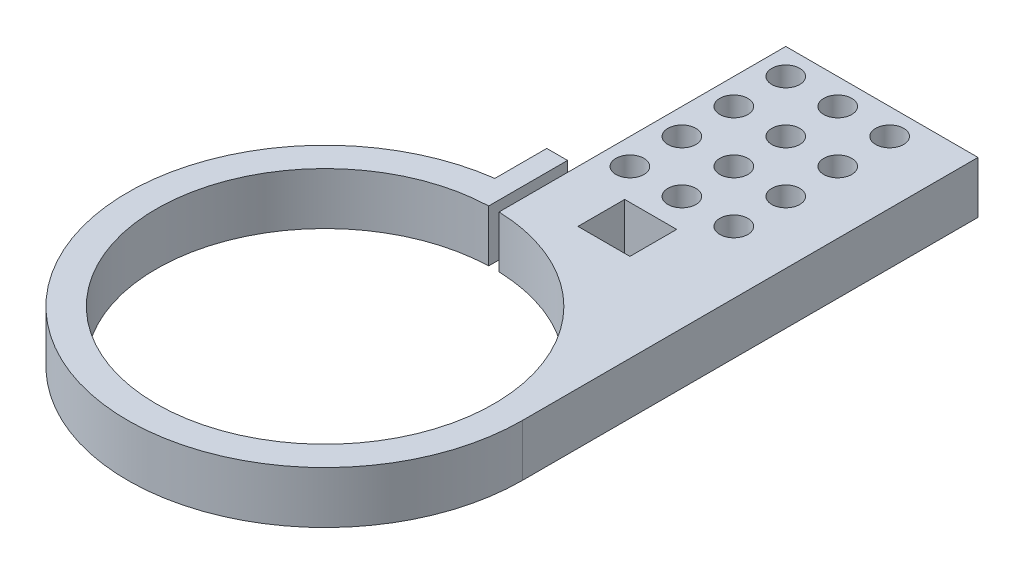
SolidWorks part; units mm, degrees
ref_plane "Front Plane" through (0, 0, 0) normal (0, 0, 1) x (1, 0, 0)
ref_plane "Top Plane" through (0, 0, 0) normal (0, 1, 0) x (1, 0, 0)
ref_plane "Right Plane" through (0, 0, 0) normal (1, 0, 0) x (0, 0, -1)
sketch "Sketch1" plane through (0, 0, 0) normal (0, 1, 0) x (1, 0, 0)
  circle A0 centre (0, 0) radius 41.275
  circle A1 centre (0, 0) radius 48.26
  dimension "D1" = 82.55
  dimension "D2" = 96.52
extrude "Boss-Extrude1" add sketch "Sketch1" along normal blind 12.7
sketch "Sketch2" plane through (0, 0, 0) normal (0, 1, 0) x (1, 0, 0)
  line L1 (6.35, 60.5404) -> (-6.35, 60.5404)
  line L2 (6.35, 60.5404) -> (6.35, 47.8404)
  line L3 (6.35, 47.8404) -> (-6.35, 47.8404)
  line L4 (-6.35, 60.5404) -> (-6.35, 47.8404)
  line L5 (6.35, 60.5404) -> (-6.35, 47.8404) construction
  line L6 (6.35, 47.8404) -> (-6.35, 60.5404) construction
  circle A0 centre (0, 0) radius 48.26 construction
  point P0 (0, 54.1904)
  dimension "D1" = 12.7
  dimension "D2" = 12.7
extrude "Boss-Extrude2" add sketch "Sketch2" along normal blind 12.7
sketch "Sketch4" plane through (0, 0, 0) normal (0, 1, 0) x (1, 0, 0)
  line L1 (-1.27, 38.0719) -> (1.27, 38.0719)
  line L2 (-1.27, 38.0719) -> (-1.27, 82.1708)
  line L3 (-1.27, 82.1708) -> (1.27, 82.1708)
  line L4 (1.27, 38.0719) -> (1.27, 82.1708)
  line L5 (-1.27, 38.0719) -> (1.27, 82.1708) construction
  line L6 (-1.27, 82.1708) -> (1.27, 38.0719) construction
  point P0 (0, 60.1213)
  point P5 (0, 82.1708)
  dimension "D1" = 2.54
extrude "Cut-Extrude2" cut sketch "Sketch4" along normal through all
sketch "Sketch5" plane through (0, 0, 0) normal (1, 0, 0) x (0, 0, -1)
  line L1 (60.5404, 12.7) -> (0, 12.7)
  line L2 (60.5404, 12.7) -> (60.5404, 0)
  line L3 (60.5404, 0) -> (0, 0)
  line L4 (0, 12.7) -> (0, 0)
extrude "Boss-Extrude3" add sketch "Sketch5" against normal up to next from offset 48.26
sketch "Sketch6" plane through (0, 12.7, 0) normal (0, 1, 0) x (1, 0, 0)
  line L0 (1.27, 41.2555) -> (1.27, 60.5404) construction
  line L1 (48.26, 60.5404) -> (1.27, 60.5404)
  line L2 (48.26, 60.5404) -> (48.26, 111.3404)
  line L3 (48.26, 111.3404) -> (1.27, 111.3404)
  line L4 (1.27, 60.5404) -> (1.27, 111.3404)
  dimension "D1" = 50.8
extrude "Boss-Extrude4" add sketch "Sketch6" against normal blind 12.7
sketch "Sketch7" plane through (0, 0, 0) normal (0, 1, 0) x (1, 0, 0)
  line L0 (48.26, 111.3404) -> (1.27, 111.3404) construction
  line L2 (1.27, 41.2555) -> (1.27, 111.3404) construction
  line L4 (13.97, 59.2704) -> (26.67, 59.2704)
  line L5 (13.97, 59.2704) -> (13.97, 47.8404)
  line L6 (13.97, 47.8404) -> (26.67, 47.8404)
  line L7 (26.67, 59.2704) -> (26.67, 47.8404)
  circle A0 centre (7.62, 104.9904) radius 3.429
  circle A1 centre (20.32, 104.9904) radius 3.429
  circle A2 centre (20.32, 92.2904) radius 3.429
  circle A3 centre (7.62, 92.2904) radius 3.429
  circle A4 centre (7.62, 79.5904) radius 3.429
  circle A5 centre (20.32, 79.5904) radius 3.429
  circle A6 centre (7.62, 66.8904) radius 3.429
  circle A7 centre (20.32, 66.8904) radius 3.429
  circle A8 centre (33.02, 104.9904) radius 3.429
  circle A9 centre (33.02, 92.2904) radius 3.429
  circle A10 centre (33.02, 79.5904) radius 3.429
  circle A11 centre (33.02, 66.8904) radius 3.429
  dimension "D1" = 6.858
  dimension "D9" = 12.7
  dimension "D10" = 12.7
  dimension "D2" = 6.35
  dimension "D3" = 6.35
  dimension "D6" = 11.43
  dimension "D7" = 12.7
  dimension "D8" = 12.7
  dimension "D4" = 3
  dimension "D5" = 4
extrude "Cut-Extrude3" cut sketch "Sketch7" along normal through all
